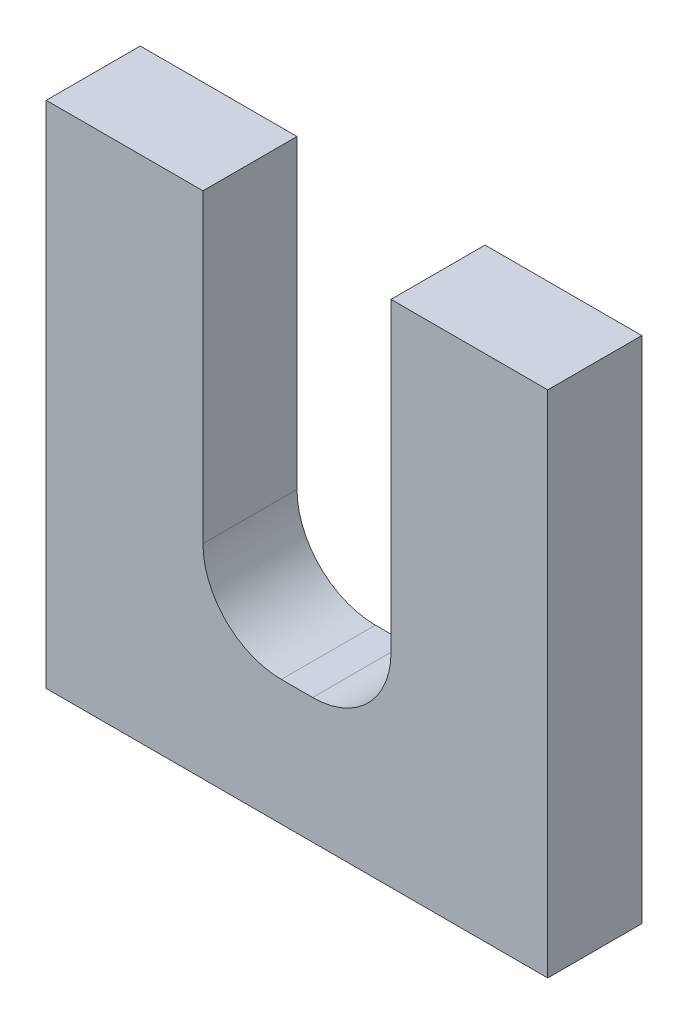
SolidWorks part; units mm, degrees
material "3.0517 (EN-AW 3003)"
ref_plane "Front Plane" through (0, 0, 0) normal (0, 0, 1) x (1, 0, 0)
ref_plane "Top Plane" through (0, 0, 0) normal (0, 1, 0) x (1, 0, 0)
ref_plane "Right Plane" through (0, 0, 0) normal (1, 0, 0) x (0, 0, -1)
sketch "Sketch1" plane through (0, 0, 0) normal (0, 0, 1) x (1, 0, 0)
  line L1 (8, -8.125) -> (-8, -8.125)
  line L2 (8, -8.125) -> (8, 8.125)
  line L3 (8, 8.125) -> (3, 8.125)
  line L4 (-8, -8.125) -> (-8, 8.125)
  line L5 (8, -8.125) -> (-8, 8.125) construction
  line L6 (8, 8.125) -> (-8, -8.125) construction
  line L9 (-3, 8.125) -> (-8, 8.125)
  line L10 (-3, 8.125) -> (-3, -1.625)
  line L11 (-0.5, -4.125) -> (0.5, -4.125)
  line L12 (3, -1.625) -> (3, 8.125)
  arc A0 (0.5, -4.125) -> (3, -1.625) centre (0.5, -1.625) ccw
  arc A1 (-3, -1.625) -> (-0.5, -4.125) centre (-0.5, -1.625) ccw
  point P0 (0, 0)
  dimension "D4" = 2.5
  dimension "D1" = 16
  dimension "D2" = 16.25
  dimension "D3" = 5
  dimension "D5" = 12.25
  dimension "D6" = 6
extrude "Boss-Extrude1" add sketch "Sketch1" along normal mid plane 3
